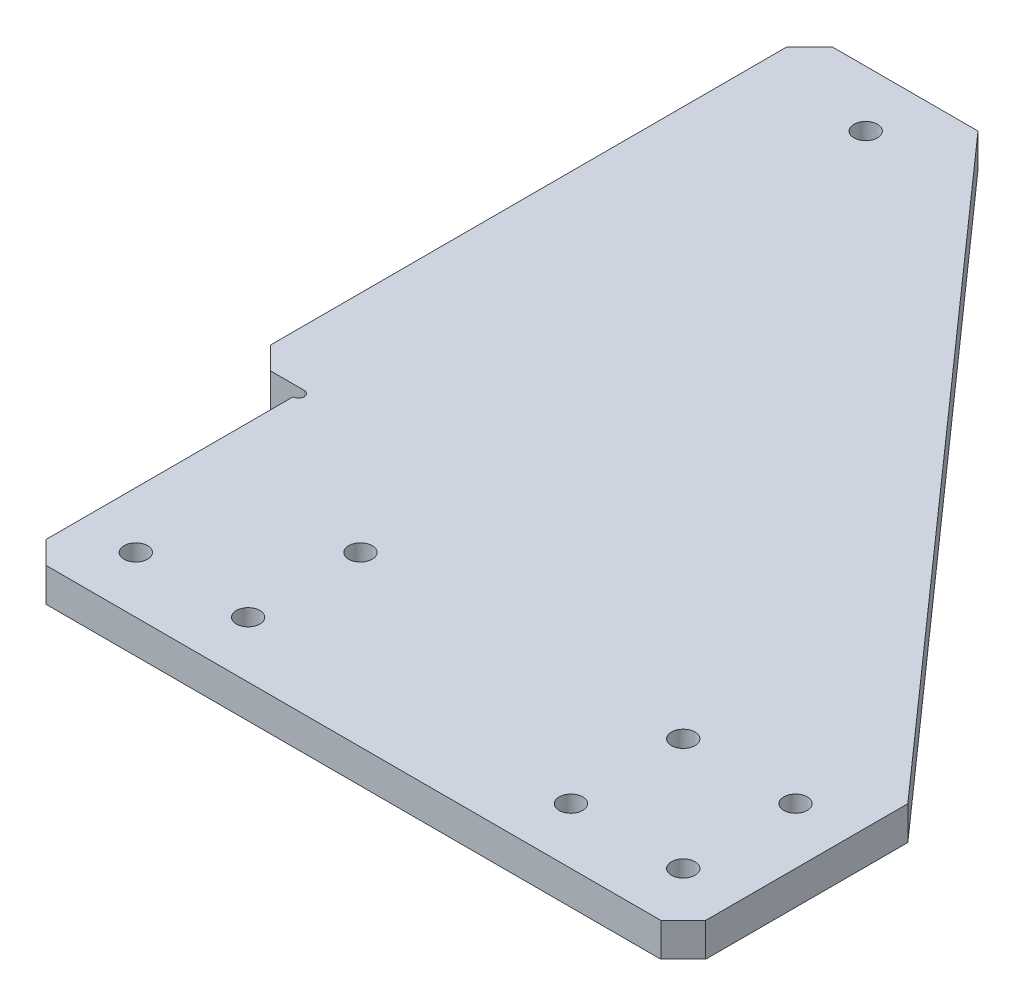
SolidWorks part; units mm, degrees
ref_plane "前视基准面" through (0, 0, 0) normal (0, 0, 1) x (1, 0, 0)
ref_plane "上视基准面" through (0, 0, 0) normal (0, 1, 0) x (1, 0, 0)
ref_plane "右视基准面" through (0, 0, 0) normal (1, 0, 0) x (0, 0, -1)
sketch "草图1" plane through (0, 0, 0) normal (0, 1, 0) x (1, 0, 0)
  line L0 (-68.75, 150) -> (-68.75, 50)
  line L1 (-58.75, 0) -> (58.75, 0)
  line L2 (58.75, 0) -> (58.75, 40)
  line L3 (58.75, 40) -> (-38.75, 150)
  line L4 (-38.75, 150) -> (-68.75, 150)
  line L5 (-48.75, 140) -> (-48.75, 10) construction
  line L6 (48.75, 30) -> (48.75, 10) construction
  line L7 (28.75, 10) -> (-28.75, 10) construction
  line L8 (28.75, 10) -> (28.75, 30) construction
  line L9 (28.75, 30) -> (-28.75, 30) construction
  line L10 (-28.75, 10) -> (-28.75, 30) construction
  line L11 (28.75, 10) -> (-28.75, 30) construction
  line L12 (28.75, 30) -> (-28.75, 10) construction
  line L13 (-68.75, 50) -> (-58.75, 50)
  line L14 (-58.75, 50) -> (-58.75, 0)
  circle A0 centre (-48.75, 140) radius 2.1
  circle A2 centre (-48.75, 10) radius 2.1
  circle A3 centre (-28.75, 30) radius 2.1
  circle A4 centre (28.75, 30) radius 2.1
  circle A5 centre (-28.75, 10) radius 2.1
  circle A6 centre (28.75, 10) radius 2.1
  circle A7 centre (48.75, 30) radius 2.1
  circle A8 centre (48.75, 10) radius 2.1
  point P12 (0, 20)
  dimension "D5" = 4.2
  dimension "D6" = 10
  dimension "D9" = 10
  dimension "D12" = 10
  dimension "D1" = 127.5
  dimension "D2" = 40
  dimension "D3" = 30
  dimension "D4" = 150
  dimension "D7" = 10
  dimension "D8" = 20
  dimension "D10" = 20
  dimension "D11" = 20
  dimension "D13" = 10
  dimension "D14" = 50
extrude "凸台-拉伸1" add sketch "草图1" along normal mid plane 6
sketch "草图2" plane through (0, 3, 0) normal (0, 1, 0) x (1, 0, 0)
  line L0 (-58.75, 50) -> (-58.75, 0) construction
  circle A0 centre (-58.75, 49) radius 1
  dimension "D1" = 2
extrude "切除-拉伸1" cut sketch "草图2" against normal through all
chamfer "倒角1" distance 4 angle 45 4 edges at (-68.75, 0, -150) (58.75, 0, 0) (-58.75, 0, 0) (-68.75, 0, -50)
chamfer "倒角2" distance 2 angle 45 8 edges at (-48.75, -3, -137.9) (48.75, -3, -27.9) (28.75, -3, -27.9) (48.75, -3, -7.9) (28.75, -3, -7.9) (-28.75, -3, -27.9) (-28.75, -3, -7.9) (-48.75, -3, -7.9)
